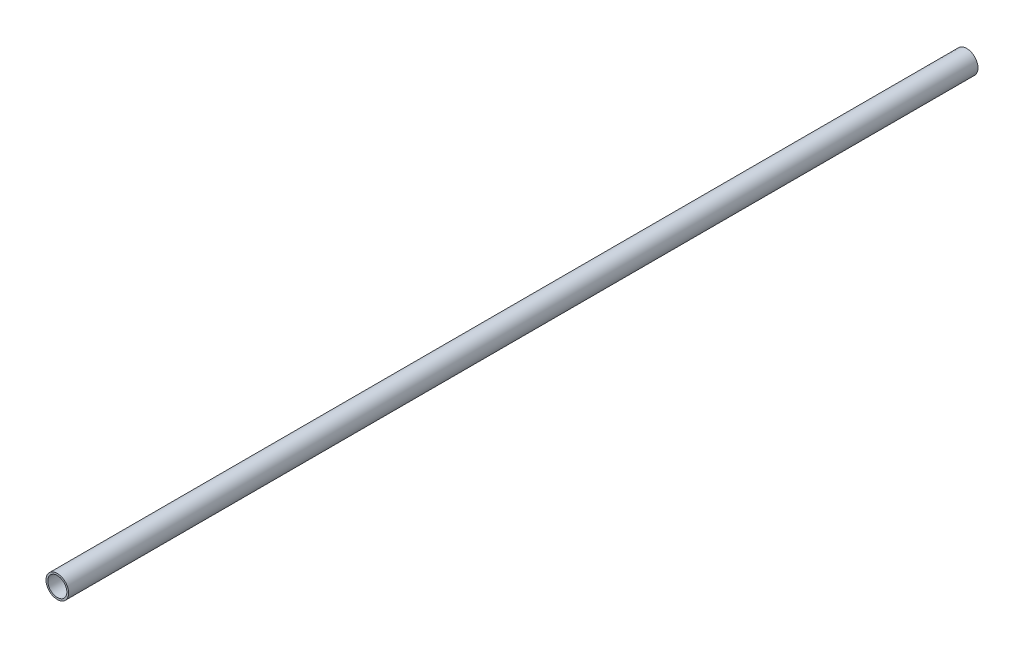
SolidWorks part; units mm, degrees
material "Thornel Mat VMA"
ref_plane "Alzado" through (0, 0, 0) normal (0, 0, 1) x (1, 0, 0)
ref_plane "Planta" through (0, 0, 0) normal (0, 1, 0) x (1, 0, 0)
ref_plane "Vista lateral" through (0, 0, 0) normal (1, 0, 0) x (0, 0, -1)
sketch "Croquis1" plane through (0, 0, 0) normal (0, 0, 1) x (1, 0, 0)
  line L0 (0, 10.7) -> (0, 12.7)
  circle A0 centre (0, 0) radius 12.7
  circle A1 centre (0, 0) radius 10.7
  dimension "D1" = 25.4
  dimension "D2" = 21.4
  dimension "D3" = 2
extrude "Saliente-Extruir1" add sketch "Croquis1" along normal blind 1020
